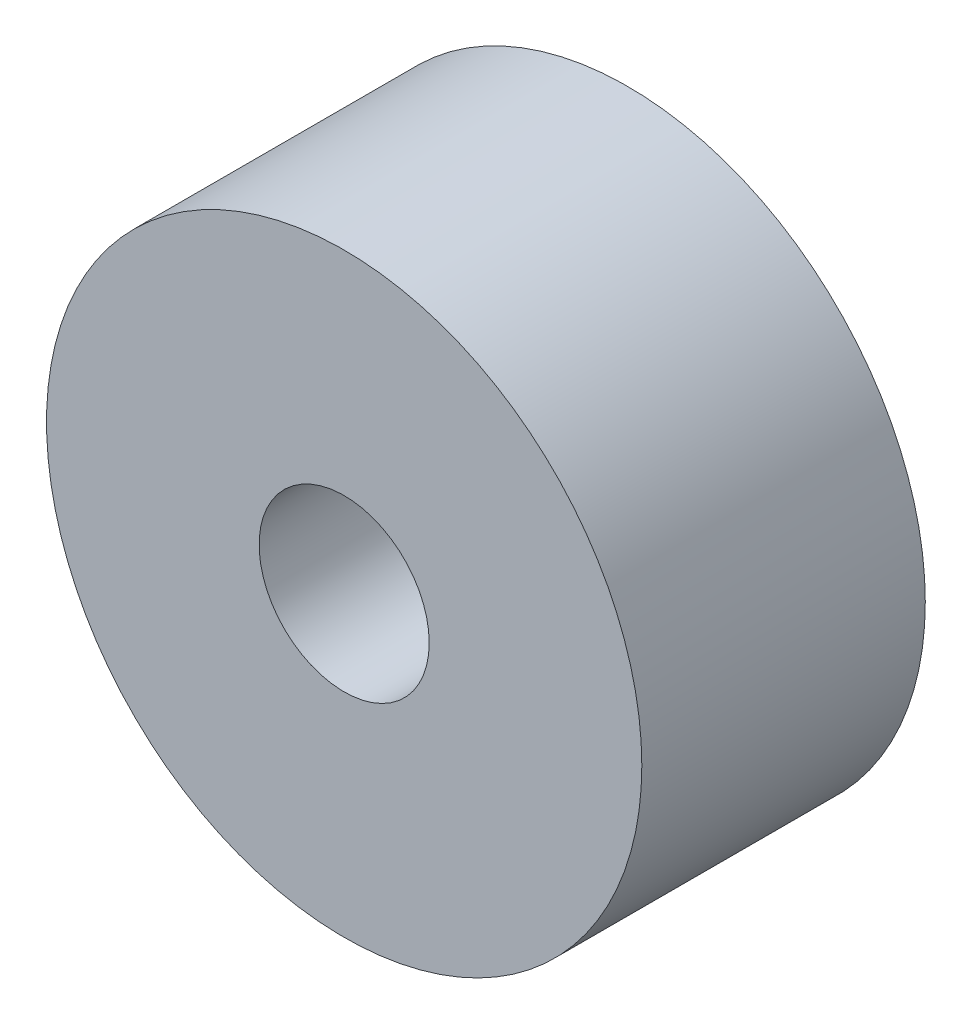
SolidWorks part; units mm, degrees
ref_plane "Płaszczyzna przednia" through (0, 0, 0) normal (0, 0, 1) x (1, 0, 0)
ref_plane "Płaszczyzna górna" through (0, 0, 0) normal (0, 1, 0) x (1, 0, 0)
ref_plane "Płaszczyzna prawa" through (0, 0, 0) normal (1, 0, 0) x (0, 0, -1)
sketch "Sketch1" plane through (0, 0, 0) normal (0, 0, 1) x (1, 0, 0)
  circle A0 centre (0, 0) radius 21
  circle A1 centre (0, 0) radius 6
  dimension "D1" = 42
  dimension "D2" = 12
extrude "Boss-Extrude1" add sketch "Sketch1" along normal mid plane 20
